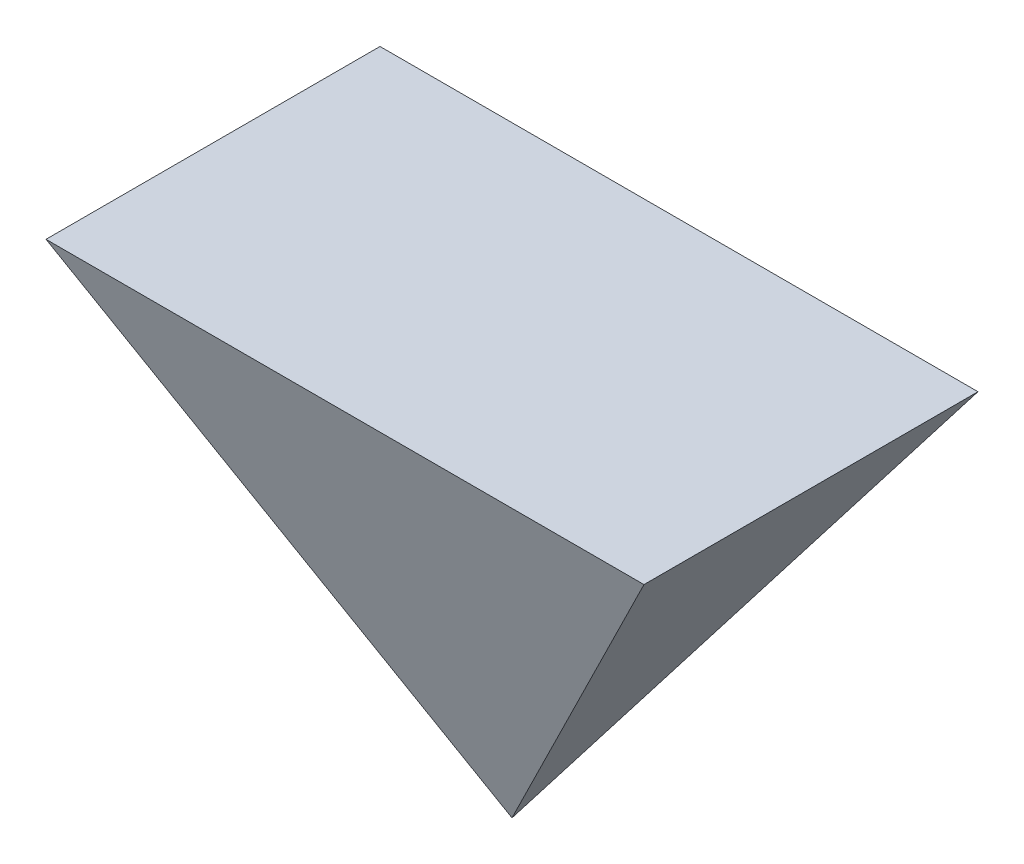
SolidWorks part; units mm, degrees
ref_plane "Front Plane" through (0, 0, 0) normal (0, 0, 1) x (1, 0, 0)
ref_plane "Top Plane" through (0, 0, 0) normal (0, 1, 0) x (1, 0, 0)
ref_plane "Right Plane" through (0, 0, 0) normal (1, 0, 0) x (0, 0, -1)
sketch "StartSquare" plane through (0, 0, 0) normal (0, 1, 0) x (1, 0, 0)
  line L5 (-1.3644, 0.7749) -> (1.3644, 0.7749)
  line L6 (-1.3644, 0.7749) -> (-1.3644, -0.7749)
  line L7 (-1.3644, -0.7749) -> (1.3644, -0.7749)
  line L8 (1.3644, 0.7749) -> (1.3644, -0.7749)
  line L9 (-1.3644, 0.7749) -> (1.3644, -0.7749) construction
  line L10 (-1.3644, -0.7749) -> (1.3644, 0.7749) construction
  point P0 (0, 0)
  dimension "D1" = 2.7288
  dimension "D2" = 1.5498
ref_plane "End" through (0, 1500, 0) normal (0, 1, 0) x (1, 0, 0)
sketch "EndSquare" plane through (0, 1500, 0) normal (0, 1, 0) x (1, 0, 0)
  line L1 (-1032.2858, 576.571) -> (1032.2858, 576.571)
  line L2 (-1032.2858, 576.571) -> (-1032.2858, -576.571)
  line L3 (-1032.2858, -576.571) -> (1032.2858, -576.571)
  line L4 (1032.2858, 576.571) -> (1032.2858, -576.571)
  line L5 (-1032.2858, 576.571) -> (1032.2858, -576.571) construction
  line L6 (-1032.2858, -576.571) -> (1032.2858, 576.571) construction
  point P0 (0, 0)
  point P6 (43.9569, -24.3067)
  point P7 (297.4454, -152.0864)
  point P8 (1031.3644, -610.3818)
  dimension "D1" = 2064.5717
  dimension "D2" = 1153.1419
loft "Frustum" add profiles "StartSquare", "EndSquare"
